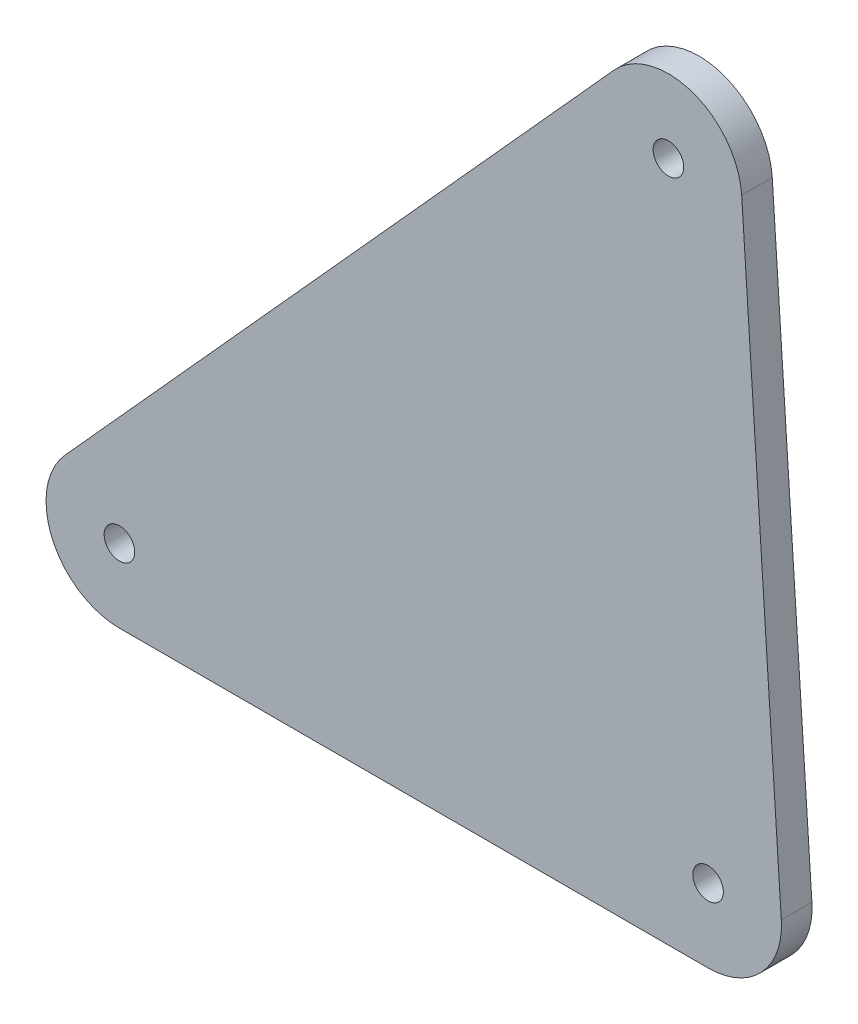
SolidWorks part; units mm, degrees
ref_plane "前视基准面" through (0, 0, 0) normal (0, 0, 1) x (1, 0, 0)
ref_plane "上视基准面" through (0, 0, 0) normal (0, 1, 0) x (1, 0, 0)
ref_plane "右视基准面" through (0, 0, 0) normal (1, 0, 0) x (0, 0, -1)
ref_plane "基准面4" through (0, 0, -18.206) normal (0, 0, 1) x (1, 0, 0)
sketch "草图1" plane through (0, 0, -18.206) normal (0, 0, 1) x (1, 0, 0)
  line L0 (108.2146, -42.9134) -> (101.7322, 56.4754)
  line L1 (80.8518, 63.7372) -> (-8.9058, -35.6516)
  line L2 (0, -55.6944) -> (96.24, -55.6944)
  circle A0 centre (89.7576, 55.6944) radius 2.5
  circle A1 centre (96.24, -43.6944) radius 2.5
  circle A2 centre (0, -43.6944) radius 2.5
  arc A3 (101.7322, 56.4754) -> (80.8518, 63.7372) centre (89.7576, 55.6944) ccw
  arc A4 (-8.9058, -35.6516) -> (0, -55.6944) centre (0, -43.6944) ccw
  arc A5 (96.24, -55.6944) -> (108.2146, -42.9134) centre (96.24, -43.6944) ccw
  point P12 (0, 0)
  point P14 (0.7086, -46.0919)
  dimension "D1" = 5
  dimension "D2" = 5
  dimension "D3" = 5
  dimension "D4" = 96.24
  dimension "D5" = 99.6
  dimension "D6" = 133.92
extrude "凸台-拉伸1" add sketch "草图1" against normal blind 5
